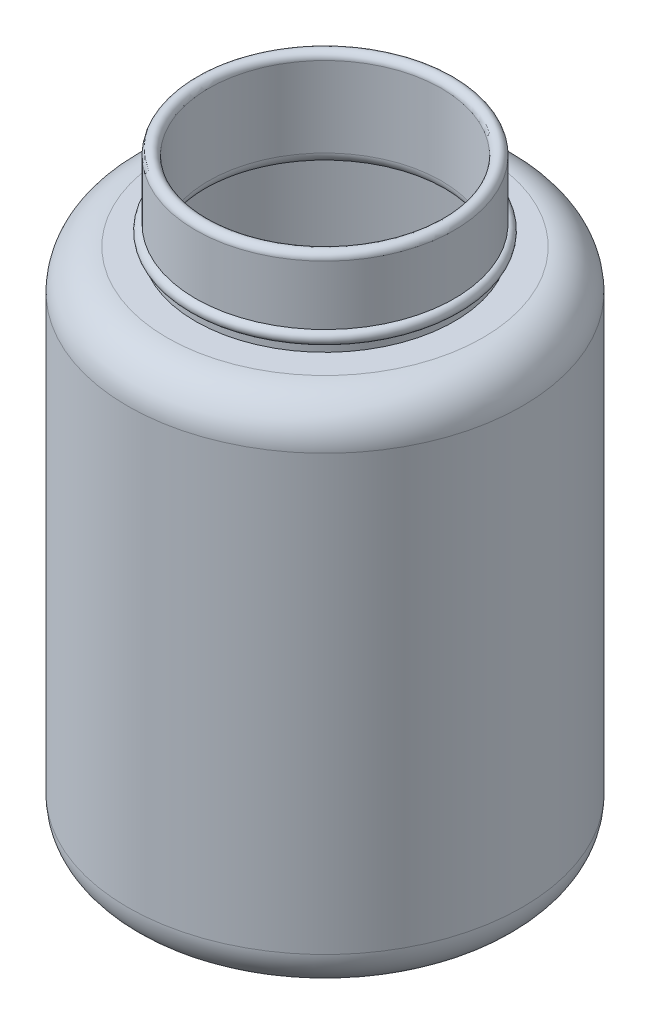
SolidWorks part; units mm, degrees
material "Vidrio"
ref_plane "Alzado" through (0, 0, 0) normal (0, 0, 1) x (1, 0, 0)
ref_plane "Planta" through (0, 0, 0) normal (0, 1, 0) x (1, 0, 0)
ref_plane "Vista lateral" through (0, 0, 0) normal (1, 0, 0) x (0, 0, -1)
sketch "Croquis1" plane through (0, 0, 0) normal (0, 0, 1) x (1, 0, 0)
  line L0 (0, 0) -> (0, 115) construction
  line L1 (0, 0) -> (40, 0)
  line L2 (50, 10) -> (50, 120)
  line L3 (40, 130) -> (32.8, 130)
  line L4 (32.8, 130) -> (32.8, 132)
  line L5 (0, 0) -> (0, 3.3)
  line L6 (32.8, 135) -> (32.8, 150)
  line L8 (29.5, 150) -> (29.5, 129.7)
  line L9 (32.5, 126.7) -> (40, 126.7)
  line L10 (0, 3.3) -> (40, 3.3)
  line L11 (46.7, 120) -> (46.7, 10)
  arc A0 (32.8, 132) -> (32.8, 135) centre (32.8, 133.5) ccw
  arc A1 (50, 120) -> (40, 130) centre (40, 120) ccw
  arc A2 (50, 10) -> (40, 0) centre (40, 10) cw
  arc A3 (40, 3.3) -> (46.7, 10) centre (40, 10) ccw
  arc A4 (46.7, 120) -> (40, 126.7) centre (40, 120) ccw
  arc A5 (29.5, 129.7) -> (32.5, 126.7) centre (32.5, 129.7) ccw
  arc A6 (29.5, 150) -> (32.8, 150) centre (31.15, 150) cw
  point P14 (50, 130)
  point P17 (50, 0)
  dimension "D2" = 1.5
  dimension "D11" = 10
  dimension "D12" = 10
  dimension "D13" = 3.3
  dimension "D14" = 3
  dimension "D15" = 3.3
  dimension "D16" = 3.3
  dimension "D1" = 115
  dimension "D3" = 2
  dimension "D4" = 50
  dimension "D5" = 130
  dimension "D6" = 15
  dimension "D7" = 29.5
  dimension "D8" = 3.3
  dimension "D9" = 17.2
  dimension "D10" = 3.3
revolve "Revolución1" add sketch "Croquis1" angle 360 about L0
